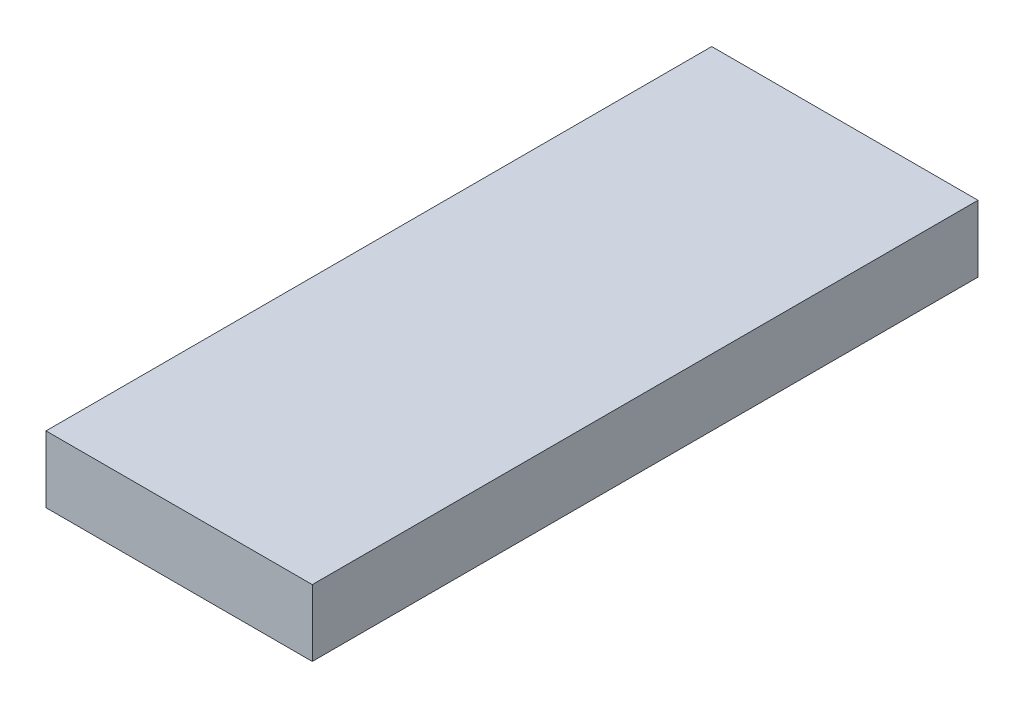
SolidWorks part; units mm, degrees
material "AISI 1020"
ref_plane "Plan de face" through (0, 0, 0) normal (0, 0, 1) x (1, 0, 0)
ref_plane "Plan de dessus" through (0, 0, 0) normal (0, 1, 0) x (1, 0, 0)
ref_plane "Plan de droite" through (0, 0, 0) normal (1, 0, 0) x (0, 0, -1)
sketch "Esquisse1" plane through (0, 0, 0) normal (0, 0, 1) x (1, 0, 0)
  line L1 (80, 20) -> (0, 20)
  line L2 (80, 20) -> (80, 0)
  line L3 (80, 0) -> (0, 0)
  line L4 (0, 20) -> (0, 0)
  dimension "D1" = 20
  dimension "D2" = 80
extrude "Boss.-Extru.1" add sketch "Esquisse1" along normal blind 200
